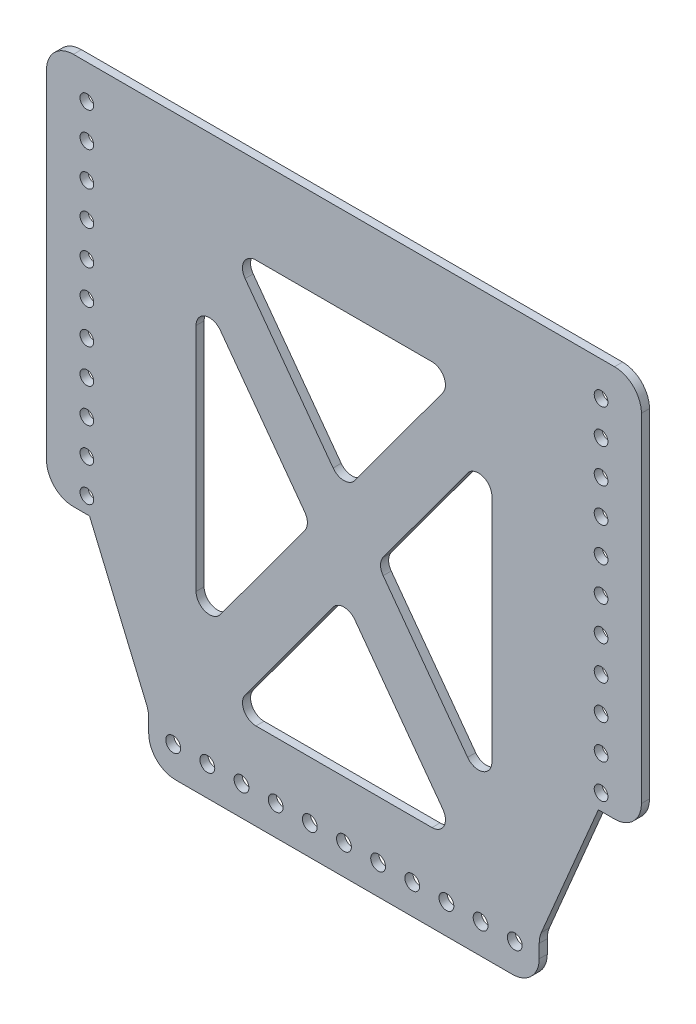
SolidWorks part; units mm, degrees
ref_plane "前视基准面" through (0, 0, 0) normal (0, 0, 1) x (1, 0, 0)
ref_plane "上视基准面" through (0, 0, 0) normal (0, 1, 0) x (1, 0, 0)
ref_plane "右视基准面" through (0, 0, 0) normal (1, 0, 0) x (0, 0, -1)
sketch "草图1" plane through (0, 0, 0) normal (0, 0, 1) x (1, 0, 0)
  line L1 (-70.9055, -130.4812) -> (150.2945, -130.4812)
  line L2 (-70.9055, -130.4812) -> (-70.9055, -348.1412)
  line L3 (-70.9055, -348.1412) -> (150.2945, -348.1412)
  line L4 (150.2945, -130.4812) -> (150.2945, -348.1412)
  circle A0 centre (-49.2055, -334.0728) radius 2.7574
  circle A1 centre (-36.5055, -334.0728) radius 2.7574
  circle A2 centre (-23.8055, -334.0728) radius 2.7574
  circle A3 centre (-11.1055, -334.0728) radius 2.7574
  circle A4 centre (1.5945, -334.0728) radius 2.7574
  circle A5 centre (14.2945, -334.0728) radius 2.7574
  circle A6 centre (26.9945, -334.0728) radius 2.7574
  circle A7 centre (39.6945, -334.0728) radius 2.7574
  circle A8 centre (52.3945, -334.0728) radius 2.7574
  circle A9 centre (65.0945, -334.0728) radius 2.7574
  circle A10 centre (77.7945, -334.0728) radius 2.7574
  circle A11 centre (90.4945, -334.0728) radius 2.7574
  circle A12 centre (103.1945, -334.0728) radius 2.7574
  circle A13 centre (115.8945, -334.0728) radius 2.7574
  circle A27 centre (-61.9055, -334.0728) radius 2.7574
  circle A28 centre (128.5945, -334.0728) radius 2.7574
  circle A29 centre (141.2945, -334.0728) radius 2.7574
  point P4 (0, 0)
  dimension "D1" = 221.2
  dimension "D2" = 14.0684
  dimension "9" = 9
  dimension "D4" = 17
  dimension "D5" = 217.66
extrude "凸台-拉伸1" add sketch "草图1" along normal blind 3
sketch "草图2" plane through (0, 0, 3) normal (0, 0, 1) x (1, 0, 0)
  line L0 (-70.9055, -130.4812) -> (-70.9055, -348.1412) construction
  line L1 (150.2945, -130.4812) -> (-70.9055, -130.4812) construction
  line L2 (39.6945, -130.4812) -> (39.6945, -348.1412) construction
  line L3 (-70.9055, -348.1412) -> (150.2945, -348.1412) construction
  circle A0 centre (-55.9055, -143.1812) radius 2.55
  circle A1 centre (-55.9055, -155.8812) radius 2.55
  circle A2 centre (-55.9055, -168.5812) radius 2.55
  circle A3 centre (-55.9055, -181.2812) radius 2.55
  circle A4 centre (-55.9055, -193.9812) radius 2.55
  circle A5 centre (-55.9055, -206.6812) radius 2.55
  circle A6 centre (-55.9055, -219.3812) radius 2.55
  circle A7 centre (-55.9055, -232.0812) radius 2.55
  circle A8 centre (-55.9055, -244.7812) radius 2.55
  circle A9 centre (-55.9055, -257.4812) radius 2.55
  circle A10 centre (-55.9055, -270.1812) radius 2.55
  circle A11 centre (-55.9055, -282.8812) radius 2.55
  circle A12 centre (-55.9055, -295.5812) radius 2.55
  circle A13 centre (-55.9055, -308.2812) radius 2.55
  circle A14 centre (-55.9055, -320.9812) radius 2.55
  circle A15 centre (135.2945, -320.9812) radius 2.55
  circle A16 centre (135.2945, -308.2812) radius 2.55
  circle A17 centre (135.2945, -295.5812) radius 2.55
  circle A18 centre (135.2945, -282.8812) radius 2.55
  circle A19 centre (135.2945, -270.1812) radius 2.55
  circle A20 centre (135.2945, -257.4812) radius 2.55
  circle A21 centre (135.2945, -244.7812) radius 2.55
  circle A22 centre (135.2945, -232.0812) radius 2.55
  circle A23 centre (135.2945, -219.3812) radius 2.55
  circle A24 centre (135.2945, -206.6812) radius 2.55
  circle A25 centre (135.2945, -193.9812) radius 2.55
  circle A26 centre (135.2945, -181.2812) radius 2.55
  circle A27 centre (135.2945, -168.5812) radius 2.55
  circle A28 centre (135.2945, -155.8812) radius 2.55
  circle A29 centre (135.2945, -143.1812) radius 2.55
  dimension "D3" = 5.1
  dimension "D1" = 15
  dimension "D2" = 12.7
  dimension "D5" = 12.7
  dimension "D4" = 15
extrude "切除-拉伸1" cut sketch "草图2" against normal blind 10
sketch "草图3" plane through (0, 0, 3) normal (0, 0, 1) x (1, 0, 0)
  line L0 (112.2945, -345.1412) -> (112.2945, -328.1412)
  line L1 (-70.9055, -348.1412) -> (150.2945, -348.1412) construction
  line L2 (112.2945, -328.1412) -> (134.2945, -276.1412)
  line L3 (134.2945, -276.1412) -> (150.2945, -276.1412)
  line L4 (150.2945, -348.1412) -> (150.2945, -130.4812) construction
  line L6 (150.2945, -348.1412) -> (150.2945, -276.1412)
  line L7 (39.6945, -130.4812) -> (39.6945, -348.1412) construction
  line L8 (150.2945, -130.4812) -> (-70.9055, -130.4812) construction
  line L9 (-70.9055, -348.1412) -> (-70.9055, -276.1412)
  line L10 (150.2945, -348.1412) -> (-70.9055, -348.1412)
  line L11 (-54.9055, -276.1412) -> (-70.9055, -276.1412)
  line L12 (-32.9055, -328.1412) -> (-54.9055, -276.1412)
  line L13 (-32.9055, -345.1412) -> (-32.9055, -328.1412)
  line L14 (-32.9055, -345.1412) -> (112.2945, -345.1412)
  line L15 (-70.9055, -130.4812) -> (-70.9055, -348.1412) construction
  point P0 (39.6945, -348.1412)
  point P16 (-32.9055, -345.1412)
  point P20 (112.2945, -348.1412)
  point P22 (149.8947, -348.1412)
  point P23 (0, 0)
  dimension "D1" = 38
  dimension "D2" = 16
  dimension "D3" = 72
  dimension "D4" = 3
  dimension "D5" = 17
extrude "切除-拉伸2" cut sketch "草图3" against normal blind 10
fillet "圆角1" radius 10 8 edges at (-70.9055, -130.4812, 1.5) (150.2945, -130.4812, 1.5) (150.2945, -276.1412, 1.5) (112.2945, -328.1412, 1.5) (112.2945, -345.1412, 1.5) (-32.9055, -345.1412, 1.5) (-32.9055, -328.1412, 1.5) (-70.9055, -276.1412, 1.5)
sketch "草图4" plane through (0, 0, 3) normal (0, 0, 1) x (1, 0, 0)
  line L0 (39.6945, -130.4812) -> (39.6945, -220.9012) construction
  line L1 (140.2945, -130.4812) -> (-60.9055, -130.4812) construction
  line L2 (102.2945, -345.1412) -> (-22.9055, -345.1412) construction
  line L3 (-15.3055, -179.7213) -> (27.2937, -237.8112)
  line L4 (-2.9048, -162.8112) -> (82.2937, -162.8112)
  line L5 (-15.3055, -179.7213) -> (-15.3055, -295.9012)
  line L6 (-2.9048, -312.8112) -> (82.2937, -312.8112)
  line L7 (94.6945, -179.7213) -> (94.6945, -295.9012)
  line L8 (52.0952, -237.8112) -> (94.6945, -295.9012)
  line L10 (-2.9048, -312.8112) -> (39.6945, -254.7213)
  line L11 (-2.9048, -162.8112) -> (39.6945, -220.9012)
  line L12 (-15.3055, -295.9012) -> (27.2937, -237.8112)
  line L19 (52.0952, -237.8112) -> (94.6945, -179.7213)
  line L20 (39.6945, -254.7213) -> (39.6945, -345.1412) construction
  line L21 (39.6945, -220.9012) -> (82.2937, -162.8112)
  line L22 (39.6945, -254.7213) -> (82.2937, -312.8112)
  point P6 (39.6945, -237.8112)
extrude "切除-拉伸3" cut sketch "草图4" against normal blind 10
fillet "圆角2" radius 5 12 edges at (-15.3055, -179.7213, 1.5) (27.2937, -237.8112, 1.5) (-15.3055, -295.9012, 1.5) (-2.9048, -312.8112, 1.5) (82.2937, -312.8112, 1.5) (39.6945, -254.7213, 1.5) (94.6945, -179.7213, 1.5) (52.0952, -237.8112, 1.5) (94.6945, -295.9012, 1.5) (39.6945, -220.9012, 1.5) (82.2937, -162.8112, 1.5) (-2.9048, -162.8112, 1.5)
